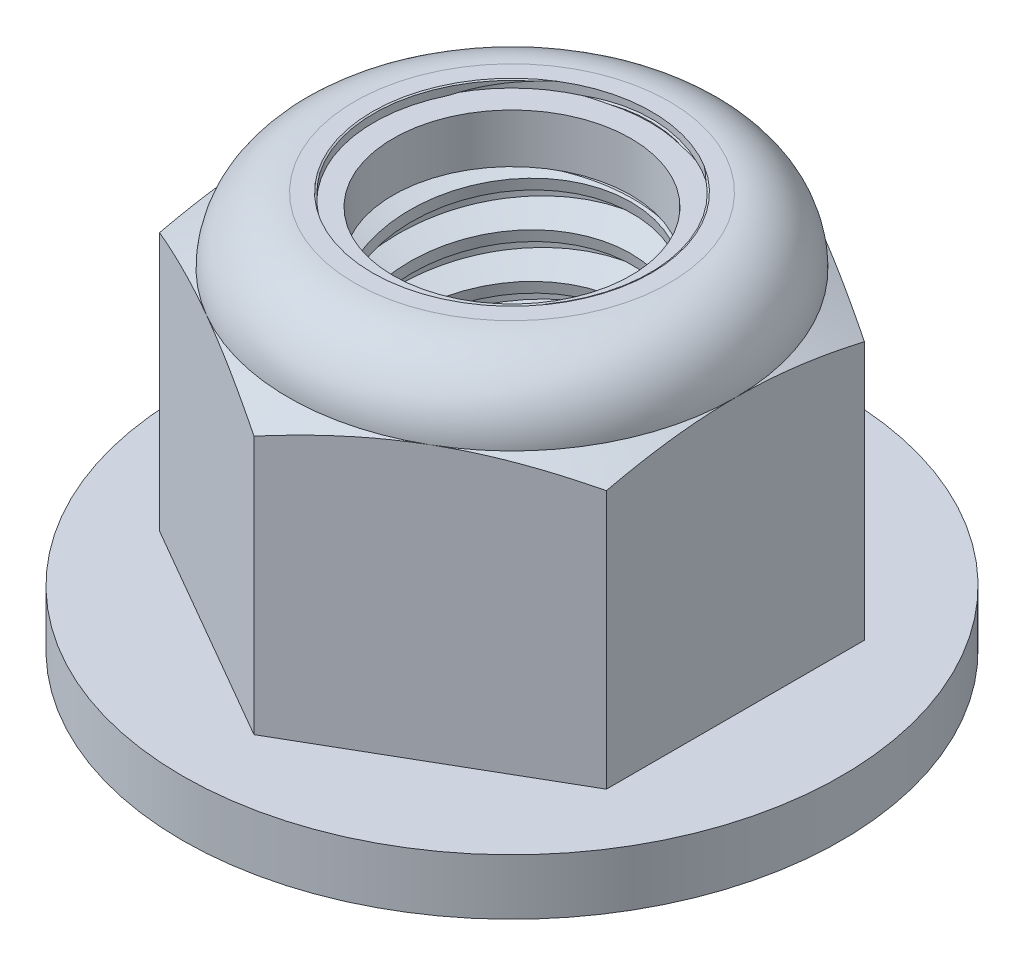
SolidWorks part; units mm, degrees
ref_plane "Front" through (0, 0, 0) normal (0, 0, 1) x (1, 0, 0)
ref_plane "Top" through (0, 0, 0) normal (0, 1, 0) x (1, 0, 0)
ref_plane "Right" through (0, 0, 0) normal (1, 0, 0) x (0, 0, -1)
sketch "Sketch1" plane through (0, 0, 0) normal (0, 1, 0) x (1, 0, 0)
  line L1 (0, 4.6188) -> (-4, 2.3094)
  line L2 (-4, 2.3094) -> (-4, -2.3094)
  line L3 (-4, -2.3094) -> (0, -4.6188)
  line L4 (0, -4.6188) -> (4, -2.3094)
  line L5 (4, -2.3094) -> (4, 2.3094)
  line L6 (4, 2.3094) -> (0, 4.6188)
  circle A0 centre (0, 0) radius 4 construction
  dimension "Hex Flats" = 8
extrude "Extrude1" add sketch "Sketch1" along normal blind 7.1
sketch "Sketch8" plane through (0, 0, 0) normal (1, 0, 0) x (0, 0, -1)
  line L0 (0, 0) -> (5.9, 0)
  line L1 (5.9, 0) -> (5.9, 1)
  line L2 (5.9, 1) -> (0, 1)
  line L3 (0, 1) -> (0, 0)
  line L4 (0, 0) -> (0, -1) construction
  dimension "Flange Height" = 1
  dimension "Flange Dia" = 11.8
revolve "Revolve3" add sketch "Sketch8" angle 360 about L4
sketch "Sketch2" plane through (0, 0, 0) normal (1, 0, 0) x (0, 0, -1)
  line L0 (-2.5, 0) -> (-2.5, 7.1) construction
  line L1 (0, 0) -> (2.5, 0)
  line L2 (0, 0) -> (0, 7.1)
  line L3 (0, 7.1) -> (2.5, 7.1)
  line L4 (2.5, 0) -> (2.5, 7.1)
  line L5 (-2.3094, 7.1) -> (2.3094, 7.1) construction
  line L7 (0, -2.5) -> (0, 0) construction
  dimension "Thread Dia" = 5
revolve "Revolve1" add sketch "Sketch2" angle 360 about L7
sketch "Sketch3" plane through (0, 0, 0) normal (1, 0, 0) x (0, 0, -1)
  line L0 (2.5, 7.1) -> (-2.5, 7.1) construction
  line L1 (-2.5, 7.1) -> (-2.5, 6.3) construction
  line L2 (-2.5, 6.3) -> (2.5, 7.1) construction
  line L3 (2.5, 7.1) -> (2.5158, 7.0013) construction
  line L4 (2.5158, 7.0013) -> (2.6264, 6.31)
  line L5 (2.6264, 6.31) -> (2.1593, 6.4885)
  line L6 (2.1593, 6.4885) -> (2.1277, 6.686)
  line L7 (2.1277, 6.686) -> (2.5158, 7.0013)
  line L8 (2.1435, 6.5872) -> (2.5711, 6.6557) construction
  line L9 (2.5, 7.1) -> (2.5, 6.6443) construction
  line L10 (2.5, 6.6443) -> (-2.5, 5.8443) construction
  line L11 (-2.5, 5.8443) -> (-2.5, 6.3) construction
  line L12 (-0.1369, 7.1) -> (0.1369, 5.3886) construction
  line L13 (-2.5, 0) -> (-2.5, 7.1) construction
  line L14 (0, 7.1) -> (2.5, 7.1) construction
  line L15 (2.5, 0) -> (2.5, 7.1) construction
  point P13 (0, 6.2443)
  dimension "D1" = 0.1
  dimension "D2" = 0.2
  dimension "Thread Pitch" = 0.8
  dimension "D4" = 60
  dimension "D5" = 0.8
revolve "Cut-Revolve1" cut sketch "Sketch3" angle 360 about L12
pattern_linear "LPattern1" count 9 spacing 0.8 along (0, -1, 0) count 2 spacing 0.8 along (0, 1, 0) of "Cut-Revolve1"
sketch "Sketch4" plane through (0, 0, 0) normal (1, 0, 0) x (0, 0, -1)
  line L0 (0, 7.1) -> (2.5, 7.1)
  line L1 (2.5, 7.1) -> (2.1277, 6.9264)
  line L2 (2.1277, 6.9264) -> (2.1277, 0.1736)
  line L3 (2.1277, 0.1736) -> (2.5, 0)
  line L4 (2.5, 0) -> (0, 0)
  line L5 (0, 0) -> (0, 7.1)
  line L6 (2.5, 0) -> (2.5, 7.1) construction
  line L7 (0, 7.1) -> (2.5, 7.1) construction
  line L8 (0, 0) -> (2.5, 0) construction
  line L9 (0, 0) -> (0, 7.1) construction
  line L10 (0, 7.1) -> (0, 7.5108) construction
  dimension "D1" = 25
revolve "Cut-Revolve2" cut sketch "Sketch4" angle 360 about L10
combine bodies "Combine1" operation type subtract main body 112 bodies to subtract 111
sketch "Sketch5" plane through (0, 0, 0) normal (1, 0, 0) x (0, 0, -1)
  line L0 (5.9, 1) -> (0, 1) construction
  line L1 (0, 0) -> (5.9, 0) construction
  line L2 (4.6188, 1) -> (4.6188, 5.6281)
  line L3 (4.6188, 5.6281) -> (4, 5.9167)
  line L4 (2.8167, 7.1) -> (2.8167, 8.37)
  line L5 (2.8167, 8.37) -> (5.8888, 8.37)
  line L6 (5.8888, 8.37) -> (5.8888, 1)
  line L9 (4, 5.9167) -> (4, 0) construction
  line L13 (4.6188, 1) -> (5.8888, 1)
  line L15 (0, 0) -> (0, 8.37) construction
  line L20 (0, 8.37) -> (2.8167, 8.37) construction
  line L22 (0, 7.1) -> (2.5, 7.1) construction
  arc A0 (4, 5.9167) -> (2.8167, 7.1) centre (2.8167, 5.9167) ccw
  dimension "D1" = 1.27
  dimension "D2" = 115
  dimension "D3" = 7.1
  dimension "D4" = 1.1833
revolve "Cut-Revolve3" cut sketch "Sketch5" angle 360 about L15
sketch "Sketch6" plane through (0, 0, 0) normal (1, 0, 0) x (0, 0, -1)
  line L0 (0, 5.9167) -> (3.8476, 5.9167)
  line L1 (2.8167, 6.9476) -> (2.4722, 6.9476)
  line L2 (0, 8.37) -> (0, 5.9167)
  line L3 (2.4722, 8.37) -> (0, 8.37)
  line L4 (0, 8.37) -> (2.8167, 8.37) construction
  line L5 (0, 0) -> (0, 8.37) construction
  line L6 (0, 8.37) -> (0, 44.323) construction
  line L7 (2.4722, 6.9476) -> (2.4722, 8.37)
  line L8 (2.8167, 7.1) -> (2.8167, 6.9476) construction
  line L9 (2.4722, 6.9476) -> (2.1277, 6.9476) construction
  line L10 (2.1277, 6.9476) -> (2.1277, 6.9264) construction
  arc A0 (3.8476, 5.9167) -> (2.8167, 6.9476) centre (2.8167, 5.9167) ccw
  arc A1 (4, 5.9167) -> (2.8167, 7.1) centre (2.8167, 5.9167) ccw construction
  dimension "D1" = 0.1524
revolve "Cut-Revolve4" cut sketch "Sketch6" angle 360 about L6
sketch "Sketch7" plane through (0, 0, 0) normal (1, 0, 0) x (0, 0, -1)
  line L0 (2.1277, 5.9929) -> (3.7684, 5.9929)
  line L1 (2.8167, 6.8714) -> (2.1277, 6.8714)
  line L2 (2.1277, 6.8714) -> (2.1277, 5.9929)
  line L3 (2.1277, 5.9929) -> (0, 5.9929) construction
  line L4 (0, 5.9929) -> (0, 6.8714) construction
  line L5 (0, 6.8714) -> (2.1277, 6.8714) construction
  line L6 (2.1277, 5.9929) -> (2.1277, 5.9167) construction
  line L7 (0, 5.9167) -> (3.8476, 5.9167) construction
  line L8 (2.8167, 6.8714) -> (2.8167, 6.9476) construction
  arc A0 (3.7684, 5.9929) -> (2.8167, 6.8714) centre (2.8167, 5.9167) ccw
  arc A2 (3.8476, 5.9167) -> (2.8167, 6.9476) centre (2.8167, 5.9167) ccw construction
  dimension "D1" = 0.0762
revolve "Revolve2" add sketch "Sketch7" angle 360 about L4
equation "\"D1@Sketch3\"=\"Thread Pitch@Sketch3\"/8"
equation "\"D2@Sketch3\"=\"Thread Pitch@Sketch3\"/4"
equation "\"D5@Sketch3\"=\"Thread Pitch@Sketch3\""
equation "\"D4@LPattern1\"=\"Thread Pitch@Sketch3\""
equation "\"D3@LPattern1\"=\"Thread Pitch@Sketch3\""
equation "\"D1@LPattern1\"=\"Height@Extrude1\"/\"Thread Pitch@Sketch3\""
equation "\"D4@Sketch5\"=\"Height@Extrude1\"/6"
